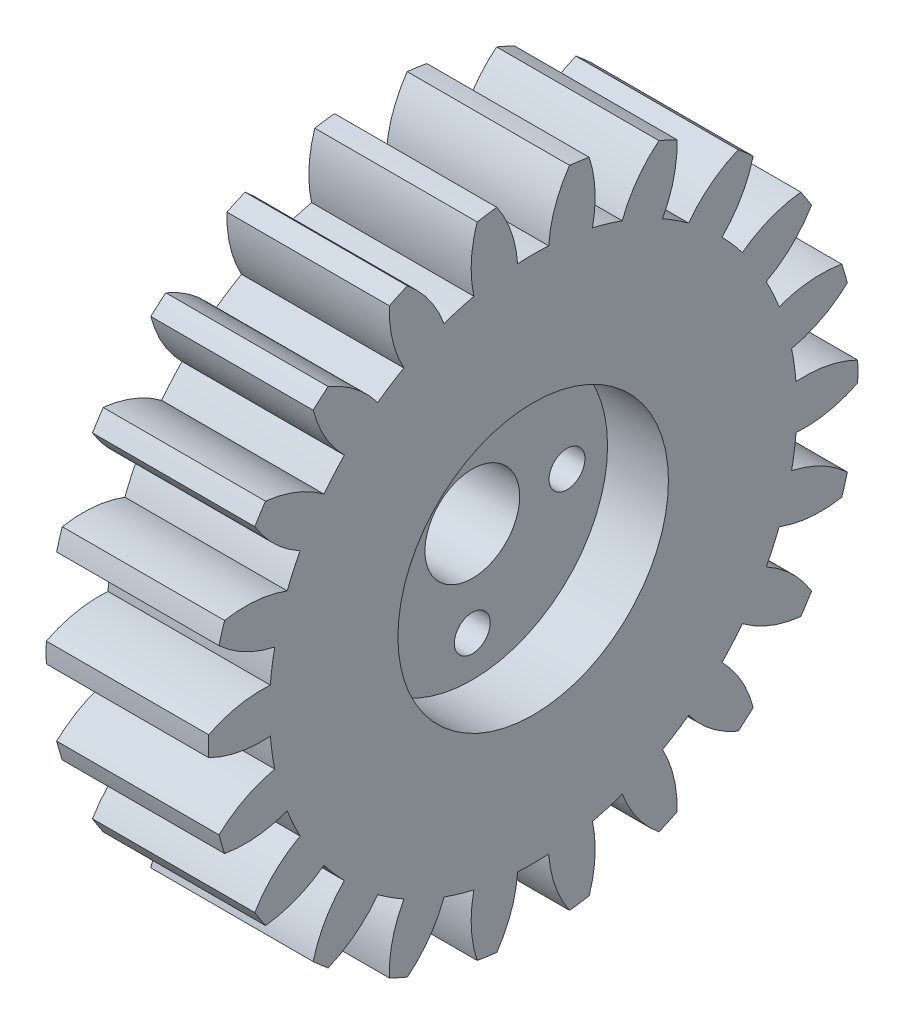
SolidWorks part; units mm, degrees
ref_plane "Plane1" through (0, 0, 0) normal (0, 0, 1) x (1, 0, 0)
ref_plane "Plane2" through (0, 0, 0) normal (0, 1, 0) x (1, 0, 0)
ref_plane "Plane3" through (0, 0, 0) normal (1, 0, 0) x (0, 0, -1)
sketch "HoldingSke" plane through (0, 0, 0) normal (0, 1, 0) x (1, 0, 0)
  line L0 (0, 0) -> (0.4636, -0.1873)
  line L1 (-15, 0) -> (100, 0) construction
  line L2 (0, 0) -> (-2.1039, 2.3779)
  line L3 (0, 0) -> (-11.863, 4.5341)
  line L4 (0, 0) -> (8.0072, 3.2351)
  line L5 (0, 0) -> (-46.8476, -17.4728)
  line L6 (0, 0) -> (-9.9476, -6.7116)
  line L7 (-2.1039, 2.3779) -> (8.6586, 51.2059)
  line L8 (-76.2, 54.61) -> (-75.2, 54.61)
  line L9 (-67.7845, 28.3722) -> (-49.3413, 33.142)
  line L10 (-76.2, 71.12) -> (104.1128, 71.12)
  line L11 (0, 0) -> (-12, 0)
  line L12 (-76.2, 101.6) -> (-76.133, 101.6)
  line L13 (24.9733, 27.94) -> (52.9518, 28.4284)
  line L14 (24.9733, 27.94) -> (24.9743, 27.94)
  line L15 (24.9733, 27.94) -> (100.4006, 29.5858)
  line L16 (-63.627, -2) -> (-12.827, -2)
  circle A0 centre (0, 0) radius 3
  circle A1 centre (0, 0) radius 19.499
  circle A2 centre (0, 0) radius 37.5
  circle A3 centre (0, 0) radius 3
  dimension "MHD" = 38.998
  dimension "Hub_dia" = 75
  dimension "Bore" = 6
  dimension "MBD" = 6
  dimension "Num_teeth" = 22
  dimension "Pitch" = 0.5
  dimension "Overall_len" = 50
  dimension "Show_teeth" = 22
  dimension "Thickness" = 12
  dimension "OAL" = 50.0001
  dimension "T_dim" = 1
  dimension "Ap" = 14.5
  dimension "H" = 19.05
  dimension "Pitch_radius" = 180.3128
  dimension "Width" = 12
  dimension "Backlash" = 0.067
  dimension "Addendum_fac" = 1
  dimension "Dedendum_fac" = 1.25
  dimension "Clearance_fac" = 0.25
  dimension "Dedendum_add" = 0.001
  dimension "Module" = 2
sketch "BasProSke" plane through (0, 0, 0) normal (0, 1, 0) x (1, 0, 0)
  line L0 (-10, 0) -> (60, 0) construction
  line L1 (0, 0) -> (0, 24)
  line L2 (0, 0) -> (12, 0)
  line L3 (12, 0) -> (12, 24)
  line L4 (12, 24) -> (0, 24)
  dimension "Thickness" = 12
  dimension "Diameter" = 48
revolve "Base-Revolve" add sketch "BasProSke" angle 360 about L0
sketch "TooCutSke" plane through (0, 0, 0) normal (1, 0, 0) x (0, 0, -1)
  line L1 (0, 0) -> (0, 107) construction
  line L2 (0, 0) -> (-1.6867, 21.9352) construction
  line L3 (0, 0) -> (-6.2482, 43.4572) construction
  line L4 (-1.6867, 21.9352) -> (-3.1241, 21.7286) construction
  arc A0 (1.1481, 19.4652) -> (-1.1481, 19.4652) centre (0, 0) ccw
  arc A1 (2.704, 23.8728) -> (-2.704, 23.8728) centre (0, 0) ccw
  circle A2 centre (0, 0) radius 22 construction
  circle A3 centre (0, 0) radius 21.2992 construction
  arc A4 (-1.1481, 19.4652) -> (-2.704, 23.8728) centre (-9.9262, 18.8449) ccw
  arc A5 (2.704, 23.8728) -> (1.1481, 19.4652) centre (9.9262, 18.8449) ccw
  dimension "Root_dia" = 38.998
  dimension "Overcut_dia" = 48.0508
  dimension "Pitch_dia" = 44
  dimension "Base_dia" = 42.5985
  dimension "Flank_rad" = 8.8
  dimension "Half_ang" = 8.182
  dimension "Half_CT" = 1.4522
extrude "ToothCut" cut sketch "TooCutSke" along normal through all
fillet "Breaks" [suppressed] radius 0.04
fillet "RootFillets" [suppressed] radius 0.501
pattern_circular "TeethCuts" count 22 every 16.364 about axis through (-10, 0, 0) along (1, 0, 0) of "ToothCut", "RootFillets", "Breaks"
sketch "HubNeaOneSke" plane through (0, 0, 0) normal (-1, 0, 0) x (0, 0, 1)
  circle A0 centre (0, 0) radius 19.499
  dimension "Diameter" = 38.998
extrude "HubNearOne" [suppressed] add sketch "HubNeaOneSke" along normal blind 38.0001
sketch "HubNeaBotSke" plane through (0, 0, 0) normal (-1, 0, 0) x (0, 0, 1)
  circle A0 centre (0, 0) radius 19.499
  dimension "Diameter" = 38.998
extrude "HubNearBoth" [suppressed] add sketch "HubNeaBotSke" along normal blind 19
ref_plane "FarPln" through (12, 0, 0) normal (1, 0, 0) x (0, 0, -1)
sketch "HubFarSke" plane through (12, 0, 0) normal (1, 0, 0) x (0, 0, -1)
  circle A0 centre (0, 0) radius 19.499
  dimension "Diameter" = 38.998
extrude "HubFar" [suppressed] add sketch "HubFarSke" along normal blind 19
sketch "BorSke" plane through (0, 0, 0) normal (1, 0, 0) x (0, 0, -1)
  circle A0 centre (0, 0) radius 3
  dimension "Diameter" = 6
extrude "Bore" cut sketch "BorSke" along normal mid plane 100.0001
sketch "KeySke" plane through (0, 0, 0) normal (1, 0, 0) x (0, 0, -1)
  line L0 (-1, 0) -> (-1, 4)
  line L1 (-1, 4) -> (1, 4)
  line L2 (1, 4) -> (1, 0)
  line L3 (0, 0) -> (0, 34) construction
  line L4 (-1, 0) -> (1, 0)
  dimension "Offset" = 4
  dimension "Width" = 2
extrude "Keyway" [suppressed] cut sketch "KeySke" along normal mid plane 100.0001
pattern_circular "Keyway2" [suppressed] count 2 every 90 about axis through (-10, 0, 0) along (1, 0, 0)
sketch "Sketch1" plane through (12, 0, 0) normal (1, 0, 0) x (0, 0, -1)
  circle A0 centre (0, 0) radius 10
  dimension "D1" = 20
extrude "Cut-Extrude1" cut sketch "Sketch1" against normal blind 4.5
sketch "Sketch2" plane through (7.5, 0, 0) normal (1, 0, 0) x (0, 0, -1)
  circle A0 centre (0, 0) radius 3.5
  dimension "D1" = 7
extrude "Cut-Extrude2" cut sketch "Sketch2" against normal up to next
sketch "Sketch3" plane through (7.5, 0, 0) normal (1, 0, 0) x (0, 0, -1)
  circle A0 centre (0, 0) radius 7 construction
  circle A1 centre (0, 7) radius 1.325
  circle A2 centre (7, 0) radius 1.325
  circle A3 centre (0, -7) radius 1.325
  circle A4 centre (-7, 0) radius 1.325
  point P14 (0, 0)
  dimension "D1" = 14
  dimension "D2" = 2.65
  dimension "D3" = 4
extrude "Cut-Extrude3" cut sketch "Sketch3" against normal up to next
equation "' \"Module@HoldingSke\" = 6.35"
equation "' \"Num_teeth@HoldingSke\" = 12"
equation "' \"Ap@HoldingSke\" =  20"
equation "' \"Ap@HoldingSke\" = 20"
equation "' \"Width@HoldingSke\" = 0.5 * 25.4"
equation "' \"Hub_dia@HoldingSke\"= 1 * 25.4"
equation "' \"Hub_dia@HoldingSke\" = 1 * 25.4"
equation "' \"Overall_len@HoldingSke\" = 1.0 * 25.4"
equation "' \"Bore@HoldingSke\" = 0.75 * 25.4"
equation "' \"T_dim@HoldingSke\" = 0.1 * 25.4"
equation "' \"Width@KeySke\" = 0.25 * 25.4"
equation "' \"Show_teeth@HoldingSke\" = 13"
equation "' \"Backlash@HoldingSke\" = 0.009 * 25.4"
equation "' \"Addendum_fac@HoldingSke\" = 1.0"
equation "' \"Dedendum_fac@HoldingSke\" = 1.25"
equation "' \"Dedendum_add@HoldingSke\" = 0.00005 * 25.4"
equation "' \"Clearance_fac@HoldingSke\" = 0.25"
equation "\"Pitch@HoldingSke\" = 1 / \"Module@HoldingSke\""
equation "\"Overcut_dia@TooCutSke\" = (\"Num_teeth@HoldingSke\" + 2 * \"Addendum_fac@HoldingSke\") / \"Pitch@HoldingSke\" + 0.002 * 25.4"
equation "\"Pitch_dia@TooCutSke\" = \"Num_teeth@HoldingSke\" / \"Pitch@HoldingSke\""
equation "\"Base_dia@TooCutSke\" = \"Num_teeth@HoldingSke\" / \"Pitch@HoldingSke\" * cos((\"Ap@HoldingSke\"  * 3.14159265 / 180))"
equation "\"Root_dia@TooCutSke\" = (\"Num_teeth@HoldingSke\" + 2) / \"Pitch@HoldingSke\" - 2 * (\"Addendum_fac@HoldingSke\" + \"Dedendum_fac@HoldingSke\") / \"Pitch@HoldingSke\" - \"Dedendum_add@HoldingSke\" * 2"
equation "\"Half_ang@TooCutSke\" = 180 / \"Num_teeth@HoldingSke\""
equation "\"Half_CT@TooCutSke\" = \"Num_teeth@HoldingSke\" / \"Pitch@HoldingSke\" * sin((3.14159265 / 2 / \"Num_teeth@HoldingSke\")) / 2 - 7 * \"Backlash@HoldingSke\" / 4"
equation "\"Flank_rad@TooCutSke\" = \"Num_teeth@HoldingSke\" / \"Pitch@HoldingSke\" / 5"
equation "\"Radius@RootFillets\" = \"Clearance_fac@HoldingSke\" / \"Pitch@HoldingSke\" + \"Dedendum_add@HoldingSke\""
equation "\"Break_rad@Breaks\" = 0.02 / \"Pitch@HoldingSke\""
equation "\"Thickness@HoldingSke\" = \"Width@HoldingSke\""
equation "\"OAL@HoldingSke\" = \"Thickness@HoldingSke\""
equation "\"MHD@HoldingSke\" = (\"Num_teeth@HoldingSke\" + 2) / \"Pitch@HoldingSke\" - 2 * (\"Addendum_fac@HoldingSke\" + \"Dedendum_fac@HoldingSke\")  / \"Pitch@HoldingSke\" - \"Dedendum_add@HoldingSke\" * 2"
equation "\"MBD@HoldingSke\" = (\"Num_teeth@HoldingSke\" + 2) / \"Pitch@HoldingSke\" - 2 * (\"Addendum_fac@HoldingSke\" + \"Dedendum_fac@HoldingSke\")  / \"Pitch@HoldingSke\" - \"Dedendum_add@HoldingSke\" * 2 - 0.002 * 25.4"
equation "\"MHD@HoldingSke\" = ((sgn( \"MHD@HoldingSke\" - \"Hub_dia@HoldingSke\" )-1)*( \"MHD@HoldingSke\" - \"Hub_dia@HoldingSke\" ))/-2+ \"Hub_dia@HoldingSke\""
equation "\"MBD@HoldingSke\" = ((sgn( \"MBD@HoldingSke\" - \"Bore@HoldingSke\" )-1)*( \"MBD@HoldingSke\" - \"Bore@HoldingSke\" ))/-2+ \"Bore@HoldingSke\""
equation "\"OAL@HoldingSke\" = ((sgn( \"OAL@HoldingSke\" - \"Overall_len@HoldingSke\" )+1)*( \"OAL@HoldingSke\" - \"Overall_len@HoldingSke\" ))/2 + \"Overall_len@HoldingSke\" + 0.000002 * 25.4"
equation "\"Num_teeth@TeethCuts\" = int( \"Show_teeth@HoldingSke\" ) + 1"
equation "\"Num_teeth@TeethCuts\" = ((sgn( \"Num_teeth@TeethCuts\" - \"Num_teeth@HoldingSke\" )-1)*( \"Num_teeth@TeethCuts\" - \"Num_teeth@HoldingSke\" ))/-2+ \"Num_teeth@HoldingSke\""
equation "\"Num_teeth@TeethCuts\" = ((sgn( \"Num_teeth@TeethCuts\" - 2.0)+1)*( \"Num_teeth@TeethCuts\" - 2.0))/2 +2.0"
equation "\"Angle@TeethCuts\" = 360.0 / \"Num_teeth@HoldingSke\""
equation "\"Diameter@BasProSke\" = (\"Num_teeth@HoldingSke\" + 2 * \"Addendum_fac@HoldingSke\") / \"Pitch@HoldingSke\""
equation "\"Thickness@BasProSke\"  = \"Thickness@HoldingSke\""
equation "' \"Fillet_rad@BasProSke\" =  \"Thickness@HoldingSke\" * 0.05"
equation "' \"Fillet_rad@BasProSke\" = \"Thickness@HoldingSke\" * 0.05"
equation "\"MHD@HoldingSke\" = ((sgn( \"MHD@HoldingSke\" - \"Root_dia@TooCutSke\" )-1)*( \"MHD@HoldingSke\" - \"Root_dia@TooCutSke\" ))/-2+ \"Root_dia@TooCutSke\""
equation "\"Diameter@HubNeaOneSke\" = \"MHD@HoldingSke\""
equation "\"Length@HubNearOne\" = \"OAL@HoldingSke\" - \"Thickness@BasProSke\""
equation "\"Diameter@HubNeaBotSke\" = \"MHD@HoldingSke\""
equation "\"Length@HubNearBoth\" = ( \"OAL@HoldingSke\" - \"Thickness@BasProSke\" ) / 2.0"
equation "\"Thickness@FarPln\" = \"Thickness@BasProSke\""
equation "\"Diameter@HubFarSke\" = \"MHD@HoldingSke\""
equation "\"Length@HubFar\" = ( \"OAL@HoldingSke\" - \"Thickness@BasProSke\" ) / 2.0"
equation "\"Diameter@BorSke\" = \"MBD@HoldingSke\""
equation "\"D1@Bore\" = \"OAL@HoldingSke\" * 2.0"
equation "\"D1@Keyway\" = \"OAL@HoldingSke\" * 2.0"
equation "\"Offset@KeySke\" = \"T_dim@HoldingSke\" + \"MBD@HoldingSke\" / 2.0"
